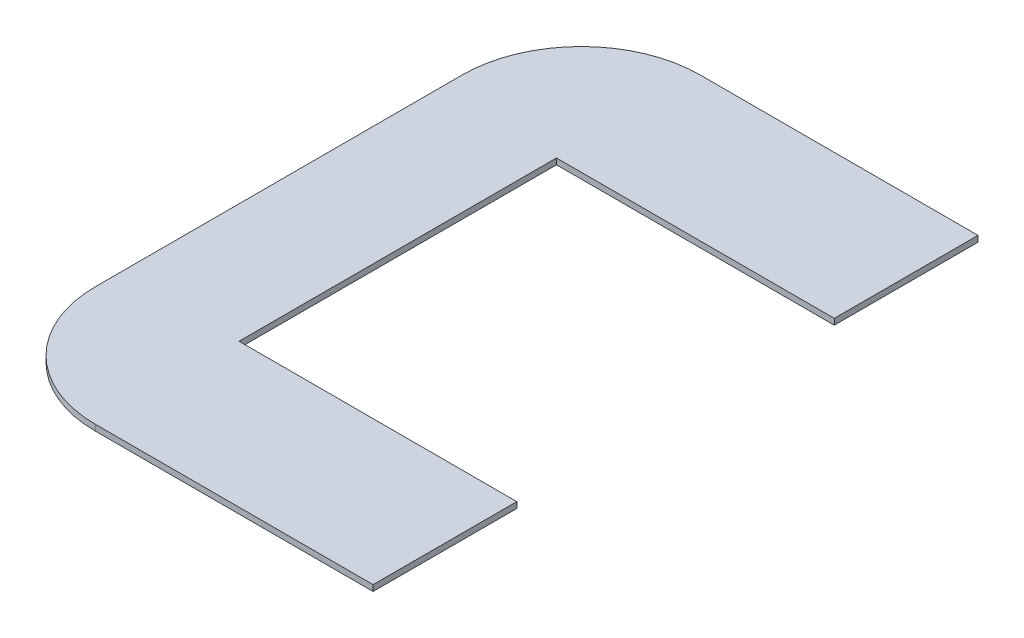
SolidWorks part; units mm, degrees
ref_plane "Alzado" through (0, 0, 0) normal (0, 0, 1) x (1, 0, 0)
ref_plane "Planta" through (0, 0, 0) normal (0, 1, 0) x (1, 0, 0)
ref_plane "Vista lateral" through (0, 0, 0) normal (1, 0, 0) x (0, 0, -1)
sketch "Croquis1" plane through (0, 0, 0) normal (0, 1, 0) x (1, 0, 0)
  line L0 (-100, 155) -> (0, 155)
  line L1 (-200, 155) -> (200, 155) construction
  line L2 (-200, 155) -> (-200, -155) construction
  line L3 (-200, -155) -> (200, -155) construction
  line L4 (200, 155) -> (200, -155) construction
  line L5 (-200, 155) -> (200, -155) construction
  line L6 (-200, -155) -> (200, 155) construction
  line L7 (-200, -155) -> (-150, -155)
  line L8 (-200, -155) -> (-200, 155)
  line L9 (-200, 155) -> (-150, 155)
  line L10 (0, -155) -> (0, 155)
  line L11 (-150, -151) -> (-100, -151) construction
  line L12 (-150, -151) -> (-150, -155) construction
  line L13 (-150, -155) -> (-100, -155) construction
  line L14 (-100, -151) -> (-100, -155) construction
  line L15 (-150, 151) -> (-100, 151) construction
  line L16 (-150, 151) -> (-150, 155) construction
  line L17 (-150, 155) -> (-100, 155) construction
  line L18 (-100, 151) -> (-100, 155) construction
  line L19 (-150, 151) -> (-100, 155) construction
  line L20 (-150, 155) -> (-100, 151) construction
  line L21 (-200, 105) -> (-196, 105) construction
  line L22 (-200, 105) -> (-200, 55) construction
  line L23 (-200, 55) -> (-196, 55) construction
  line L24 (-196, 105) -> (-196, 55) construction
  line L25 (-200, 105) -> (-196, 55) construction
  line L26 (-200, 55) -> (-196, 105) construction
  line L27 (-200, -55) -> (-196, -55) construction
  line L28 (-200, -55) -> (-200, -105) construction
  line L29 (-200, -105) -> (-196, -105) construction
  line L30 (-196, -55) -> (-196, -105) construction
  line L31 (-200, -55) -> (-196, -105) construction
  line L32 (-200, -105) -> (-196, -55) construction
  line L33 (-100, -155) -> (0, -155)
  line L34 (-200, 155) -> (-200, -155)
  line L35 (-150, 155) -> (-100, 155)
  line L36 (-150, -155) -> (-100, -155)
  point P0 (0, 0)
  point P16 (-125, 153)
  point P21 (-198, 80)
  point P26 (-198, -80)
  point P30 (-196, -105)
  dimension "D1" = 310
  dimension "D2" = 400
  dimension "D3" = 200
extrude "Saliente-Extruir1" add sketch "Croquis1" along normal blind 3 contours L9 L34 L7 L12 L11 L14 L33 L10 L0 L18 L15 L16
sketch "Croquis2" plane through (0, 3, 0) normal (0, 1, 0) x (1, 0, 0)
  line L30 (0, -155) -> (0, 155) construction
  line L31 (-200, 155) -> (0, 155)
  line L32 (-200, 155) -> (-200, 152.44)
  line L33 (-200, 152.44) -> (0, 152.44)
  line L34 (0, 155) -> (0, 152.44)
  line L35 (-200, 155) -> (0, 152.44) construction
  line L36 (-200, 152.44) -> (0, 155) construction
  line L38 (-200, -155) -> (0, -155)
  line L39 (-200, -155) -> (-200, -152.44)
  line L40 (-200, -152.44) -> (0, -152.44)
  line L41 (0, -155) -> (0, -152.44)
  line L42 (-200, -155) -> (0, -152.44) construction
  line L43 (-200, -152.44) -> (0, -155) construction
  point P5 (-100, 153.72)
  point P12 (-100, -153.72)
  dimension "D1" = 2.56
extrude "Cortar-Extruir1" cut sketch "Croquis2" against normal blind 10
sketch "Croquis3" plane through (0, 3, 0) normal (0, 1, 0) x (1, 0, 0)
  line L0 (0, -152.44) -> (0, 152.44) construction
  line L1 (-140, 80) -> (0, 80)
  line L2 (-140, 80) -> (-140, -80)
  line L3 (-140, -80) -> (0, -80)
  line L4 (0, 80) -> (0, -80)
  line L5 (-140, 80) -> (0, -80) construction
  line L6 (-140, -80) -> (0, 80) construction
  line L7 (-200, 152.44) -> (0, 152.44) construction
  line L8 (-200, -152.44) -> (-200, 152.44) construction
  point P0 (-70, 0)
  dimension "D1" = 160
  dimension "D2" = 60
  dimension "D3" = 304.88
extrude "Cortar-Extruir2" cut sketch "Croquis3" against normal blind 10
fillet "Redondeo1" radius 60 2 edges at (-200, 1.5, 152.44) (-200, 1.5, -152.44)
equation "\"D2@Croquis1\" = \"largo_tot\""
equation "\"D3@Croquis1\" = 200"
equation "\"D1@Croquis1\" = \"ancho_tot\""
equation "\"venesta\"= 4'grosor de la venesta"
equation "\"policarbonato\"= 4'grosor del policarbonato"
equation "\"carton_trupan\"= 3'grosor del carton trupan caso laser"
equation "\"ancho_tot\"= 310'ancho tot sin llantas"
equation "\"largo_tot\"= 400'largo tot sin camera"
equation "\"D1@Saliente-Extruir1\" = \"carton_trupan\""
equation "\"GROSOR_PARED_IMPRESION\"= 2.5mm"
equation "\"D1@Croquis2\"= \"GROSOR_PARED_IMPRESION\" + \"tolerancia\""
equation "\"apertura\"= 75"
equation "\"tolerancia\"= 0.06"
